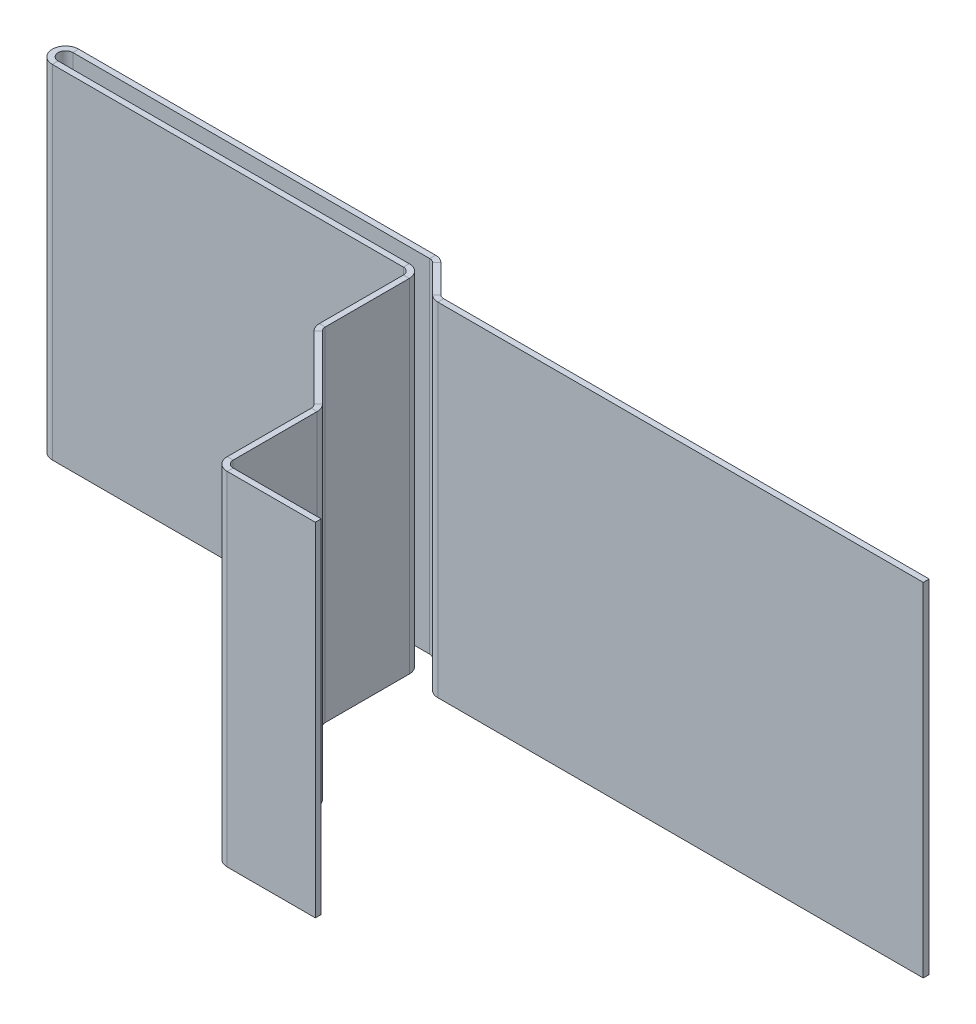
SolidWorks part; units mm, degrees
ref_plane "Front Plane" through (0, 0, 0) normal (1, 0, 0) x (0, 1, 0)
ref_plane "Top Plane" through (0, 0, 0) normal (0, 0, 1) x (0, 1, 0)
ref_plane "Right Plane" through (0, 0, 0) normal (0, 1, 0) x (-1, 0, 0)
sketch "Sketch1" plane through (0, 0, 0) normal (1, 0, 0) x (0, 1, 0)
  line L1 (35, 0.6) -> (-35, 0.6)
  line L2 (35, 0.6) -> (35, -0.6)
  line L3 (35, -0.6) -> (-35, -0.6)
  line L4 (-35, 0.6) -> (-35, -0.6)
  line L5 (35, 0.6) -> (-35, -0.6) construction
  line L6 (35, -0.6) -> (-35, 0.6) construction
  point P0 (0, 0)
  point P6 (0, 0)
  dimension "D1" = 70
  dimension "D2" = 1.2
sketch "Sketch2" plane through (0, 0, 0) normal (0, 1, 0) x (-1, 0, 0)
  line L0 (0, 0) -> (999.1716, 0)
  line L1 (1000.5858, -0.5858) -> (1006.2903, -6.2903)
  line L2 (1007.7045, -6.8761) -> (1080.607, -6.8761)
  line L3 (1080.607, -2.6761) -> (1008.8761, -2.6761)
  line L4 (1006.8761, -0.6761) -> (1006.8761, 16.4955)
  line L5 (1006.2903, 17.9097) -> (993.3197, 30.8803)
  line L6 (992.7339, 32.2945) -> (992.7339, 49.4661)
  line L7 (990.7339, 51.4661) -> (972.7339, 51.4661)
  arc A1 (1080.607, -6.8761) -> (1080.607, -2.6761) centre (1080.607, -4.7761) ccw
  arc A2 (992.7339, 49.4661) -> (990.7339, 51.4661) centre (990.7339, 49.4661) ccw
  arc A3 (993.3197, 30.8803) -> (992.7339, 32.2945) centre (994.7339, 32.2945) cw
  arc A4 (1006.8761, 16.4955) -> (1006.2903, 17.9097) centre (1004.8761, 16.4955) ccw
  arc A5 (1008.8761, -2.6761) -> (1006.8761, -0.6761) centre (1008.8761, -0.6761) cw
  arc A6 (1006.2903, -6.2903) -> (1007.7045, -6.8761) centre (1007.7045, -4.8761) ccw
  arc A7 (999.1716, 0) -> (1000.5858, -0.5858) centre (999.1716, -2) cw
  point P14 (992.7339, 51.4661)
  point P17 (992.7339, 31.4661)
  point P20 (1006.8761, 17.3239)
  point P23 (1006.8761, -2.6761)
  point P28 (1000, 0)
  dimension "D2" = 2.1
  dimension "D8" = 2
  dimension "D1" = 1000
  dimension "D3" = 20
  dimension "D4" = 135
  dimension "D5" = 20
  dimension "D6" = 20
  dimension "D7" = 20
sweep "Sweep1" add profiles "Sketch1" path "Sketch2"
sketch "Sketch4" plane through (0, 0, 0) normal (1, 0, 0) x (0, 1, 0)
  line L0 (35, 0.6) -> (35, -0.6) construction
  line L1 (-35, 0.6) -> (-35, -0.6) construction
  line L2 (35, -0.6) -> (-35, -0.6) construction
  line L3 (35, 0.6) -> (-35, 0.6) construction
  line L4 (35, 0.6) -> (35, -0.6)
  line L5 (-35, 0.6) -> (-35, -0.6)
  line L6 (35, -0.6) -> (-35, -0.6)
  line L7 (35, 0.6) -> (-35, 0.6)
  point P5 (0, 0)
extrude "Cut-Extrude3" cut sketch "Sketch4" against normal blind 900
